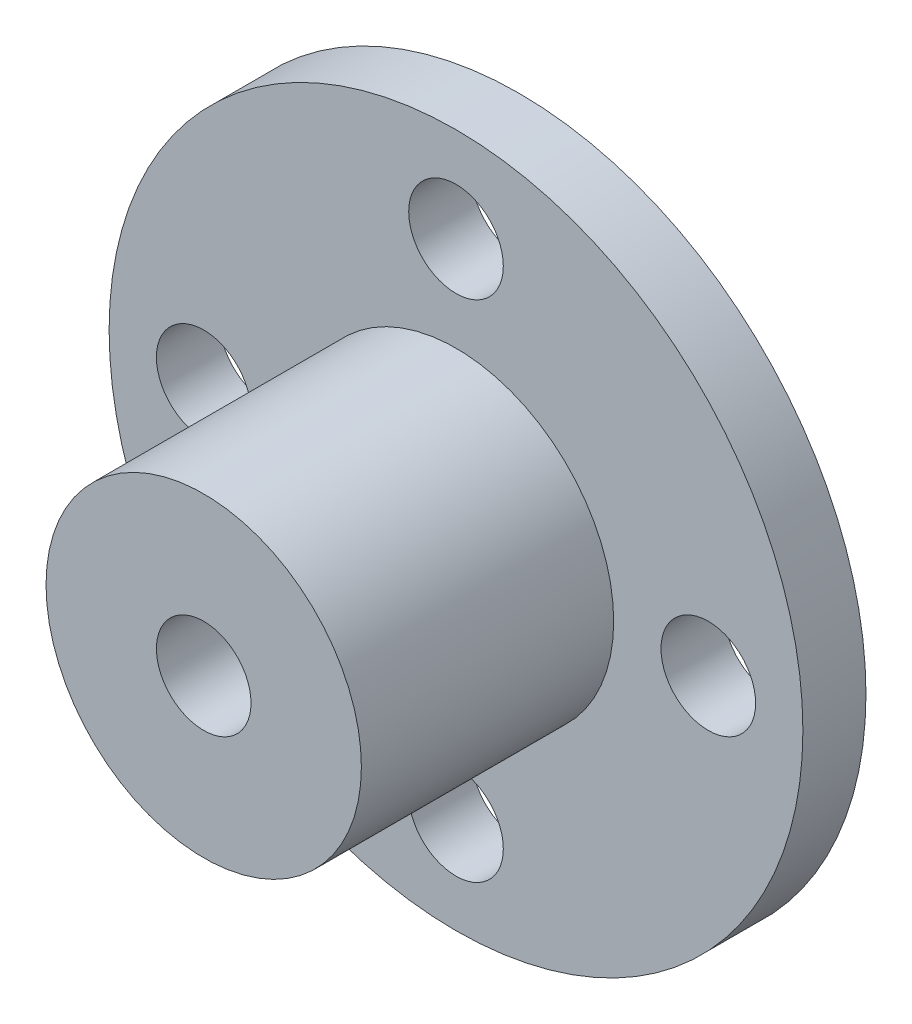
SolidWorks part; units mm, degrees
ref_plane "Front Plane" through (0, 0, 0) normal (0, 0, 1) x (1, 0, 0)
ref_plane "Top Plane" through (0, 0, 0) normal (0, 1, 0) x (1, 0, 0)
ref_plane "Right Plane" through (0, 0, 0) normal (1, 0, 0) x (0, 0, -1)
sketch "Sketch1" plane through (0, 0, 0) normal (0, 0, 1) x (1, 0, 0)
  circle A0 centre (0, 0) radius 11
extrude "Extrude1" add sketch "Sketch1" along normal blind 2
sketch "Sketch2" plane through (0, 0, 2) normal (0, 0, 1) x (1, 0, 0)
  circle A0 centre (0, 0) radius 5
extrude "Extrude2" add sketch "Sketch2" along normal blind 8
sketch "Sketch3" plane through (0, 0, 0) normal (0, 0, 1) x (1, 0, 0)
  circle A0 centre (0, 0) radius 1.5
extrude "Extrude5" cut sketch "Sketch3" along normal through all
sketch "Sketch4" plane through (0, 0, 0) normal (0, 0, -1) x (-1, 0, 0)
  line L0 (0, 0) -> (8, 0) construction
  circle A0 centre (0, 0) radius 8 construction
  circle A1 centre (8, 0) radius 1.5
  circle A2 centre (0, -8) radius 1.5
  circle A3 centre (-8, 0) radius 1.5
  circle A4 centre (0, 8) radius 1.5
  point P14 (0, 0)
  dimension "D1" = 4
extrude "Extrude6" cut sketch "Sketch4" against normal blind 8
